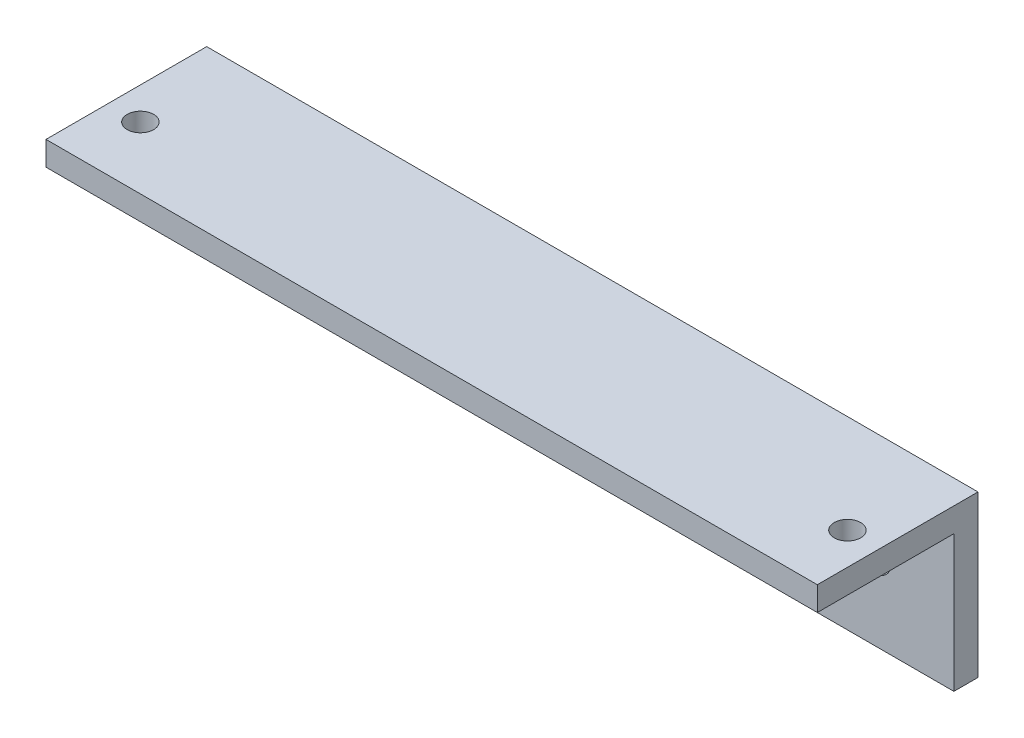
SolidWorks part; units mm, degrees
ref_plane "정면" through (0, 0, 0) normal (0, 0, 1) x (1, 0, 0)
ref_plane "윗면" through (0, 0, 0) normal (0, 1, 0) x (1, 0, 0)
ref_plane "우측면" through (0, 0, 0) normal (1, 0, 0) x (0, 0, -1)
sketch "스케치1" plane through (0, 0, 0) normal (0, 0, 1) x (1, 0, 0)
  line L1 (-48, 10) -> (48, 10)
  line L2 (-48, 10) -> (-48, -10)
  line L3 (-48, -10) -> (48, -10)
  line L4 (48, 10) -> (48, -10)
  line L5 (-48, 10) -> (48, -10) construction
  line L6 (-48, -10) -> (48, 10) construction
  point P0 (0, 0)
  dimension "D1" = 20
  dimension "D2" = 96
extrude "보스-돌출1" add sketch "스케치1" along normal blind 3
sketch "스케치2" plane through (0, 0, 3) normal (0, 0, 1) x (1, 0, 0)
  line L0 (48, -10) -> (48, 10) construction
  line L1 (-48, 10) -> (48, 10)
  line L2 (-48, 10) -> (-48, 7)
  line L3 (-48, 7) -> (48, 7)
  line L4 (48, 10) -> (48, 7)
  dimension "D1" = 3
extrude "보스-돌출2" add sketch "스케치2" along normal blind 17
hole_wizard "M4 여유 구멍1" positions "스케치3" profile "스케치5" hole size "M4" standard "KS" end condition through all
sketch "스케치3" plane through (0, 0, 3) normal (0, 0, 1) x (1, 0, 0)
  line L0 (-48, -10) -> (48, -10) construction
  line L1 (48, -10) -> (48, 7) construction
  line L2 (-48, 7) -> (-48, -10) construction
  point P0 (-38, 0)
  point P2 (38, 0)
  dimension "D1" = 10
  dimension "D2" = 10
  dimension "D3" = 10
  dimension "D4" = 10
sketch "스케치5" plane through (-38, 0, 3) normal (1, 0, 0) x (0, -1, 0)
  line L0 (0, 0) -> (0, 3)
  line L1 (0, 3) -> (2.25, 3)
  line L2 (2.25, 3) -> (2.25, 0)
  line L5 (2.25, 0) -> (0, 0)
  line L11 (0, -6.35) -> (0, 107.95) construction
  dimension "관통 구멍 지름" = 4.5
  dimension "관통 구멍 깊이" = 3
hole_wizard "M4 나사 구멍1" positions "스케치6" profile "스케치7" tap size "M4" standard "KS" end condition through all
sketch "스케치6" plane through (0, 10, 0) normal (0, 1, 0) x (1, 0, 0)
  line L0 (-48, -20) -> (-48, 0) construction
  line L1 (48, -20) -> (48, 0) construction
  line L2 (48, -20) -> (-48, -20) construction
  point P0 (-44, -12.25)
  point P2 (44, -12.25)
  dimension "D1" = 4
  dimension "D2" = 4
  dimension "D3" = 7.75
  dimension "D4" = 7.75
sketch "스케치7" plane through (-44, 10, 12.25) normal (1, 0, 0) x (0, 0, 1)
  line L0 (0, 0) -> (0, 20)
  line L1 (0, 20) -> (1.65, 20)
  line L2 (1.65, 20) -> (1.65, 0)
  line L5 (1.65, 0) -> (0, 0)
  line L11 (0, -6.35) -> (0, 107.95) construction
  dimension "관통 탭 드릴 지름" = 3.3
  dimension "관통 탭 드릴 깊이" = 20
cosmetic thread "구멍 나사산3"
cosmetic thread "구멍 나사산4"
